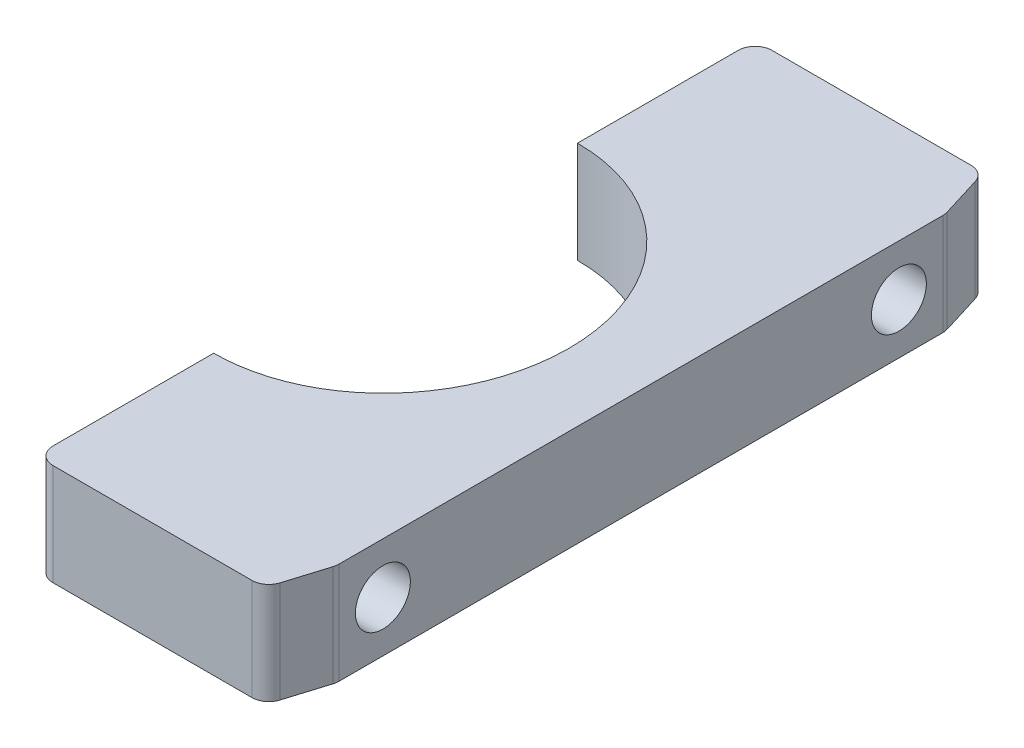
SolidWorks part; units mm, degrees
ref_plane "前基準面" through (0, 0, 0) normal (0, 0, 1) x (1, 0, 0)
ref_plane "上基準面" through (0, 0, 0) normal (0, 1, 0) x (1, 0, 0)
ref_plane "右基準面" through (0, 0, 0) normal (1, 0, 0) x (0, 0, -1)
sketch "草圖1" plane through (0, 0, 0) normal (0, 1, 0) x (1, 0, 0)
  line L0 (0, 0) -> (88.1977, 0) construction
  line L1 (0, 21.5) -> (0, 42.5)
  line L2 (0, 42.5) -> (27, 42.5)
  line L3 (27, 42.5) -> (29, 36)
  line L4 (29, 36) -> (29, -36)
  line L5 (27, -42.5) -> (29, -36)
  line L6 (0, -42.5) -> (27, -42.5)
  line L7 (0, -21.5) -> (0, -42.5)
  ellipse E0 centre (0, 0) end of major axis (0, 21.5) minor radius 20.5 (0, -21.5) -> (0, 21.5) ccw
  point P9 (29, 0)
  dimension "D1" = 41
  dimension "D2" = 43
  dimension "D3" = 85
  dimension "D4" = 29
  dimension "D5" = 27
  dimension "D6" = 72
extrude "填料-伸長1" add sketch "草圖1" along normal blind 12
fillet "圓角1" radius 2 2 edges at (29, 6, 36) (27, 6, 42.5)
fillet "圓角2" radius 2 4 edges at (0, 6, -42.5) (0, 6, 42.5) (27, 6, -42.5) (29, 6, -36)
sketch "草圖2" plane through (29, 0, 0) normal (1, 0, 0) x (0, 0, -1)
  line L0 (42.5, 12) -> (42.5, 0) construction
  line L1 (0, 6) -> (55.2851, 6) construction
  line L2 (-35.6993, 0) -> (35.6993, 0) construction
  line L3 (-35.6993, 12) -> (35.6993, 12) construction
  line L4 (0, 0) -> (0, 21.4164) construction
  circle A0 centre (30.5, 6) radius 3.25
  circle A1 centre (-30.5, 6) radius 3.25
  dimension "D2" = 6.5
  dimension "D1" = 12
extrude "除料-伸長1" cut sketch "草圖2" against normal through all
